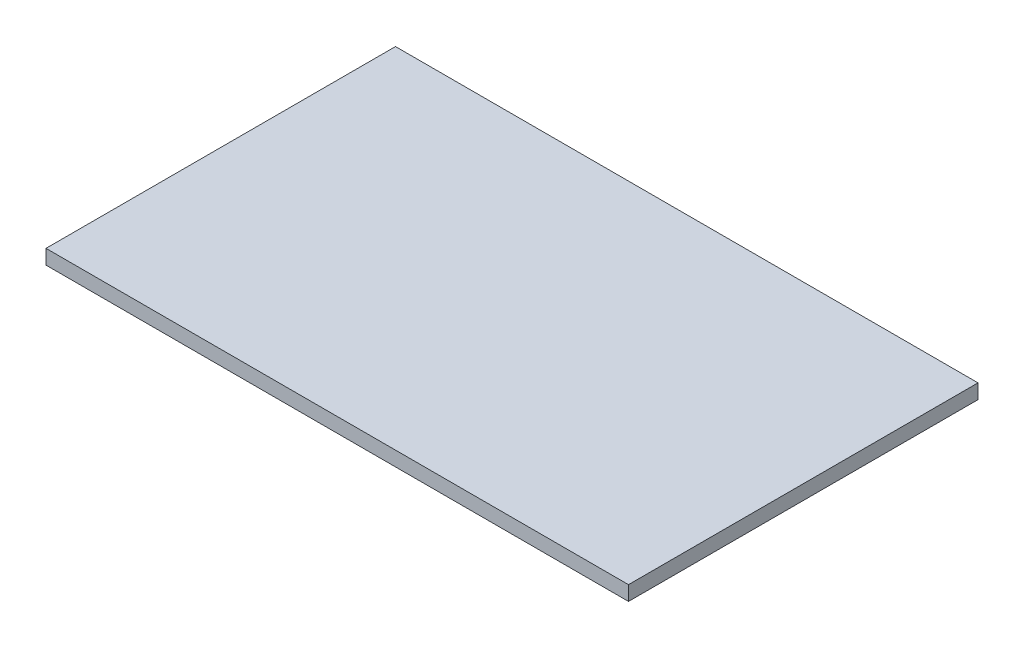
SolidWorks part; units mm, degrees
ref_plane "Ön Düzlem" through (0, 0, 0) normal (0, 0, 1) x (1, 0, 0)
ref_plane "Üst Düzlem" through (0, 0, 0) normal (0, 1, 0) x (1, 0, 0)
ref_plane "Sağ Düzlem" through (0, 0, 0) normal (1, 0, 0) x (0, 0, -1)
sketch "Çizim1" plane through (0, 0, 0) normal (0, 1, 0) x (1, 0, 0)
  line L1 (0, 0) -> (200, 0)
  line L2 (0, 0) -> (0, 120)
  line L3 (0, 120) -> (200, 120)
  line L4 (200, 0) -> (200, 120)
  dimension "D1" = 200
  dimension "D2" = 120
extrude "Yükseklik-Ekstrüzyon1" add sketch "Çizim1" along normal blind 5
scale "Scale3" scale about centroid uniform scaling yes scale factor 0.6
